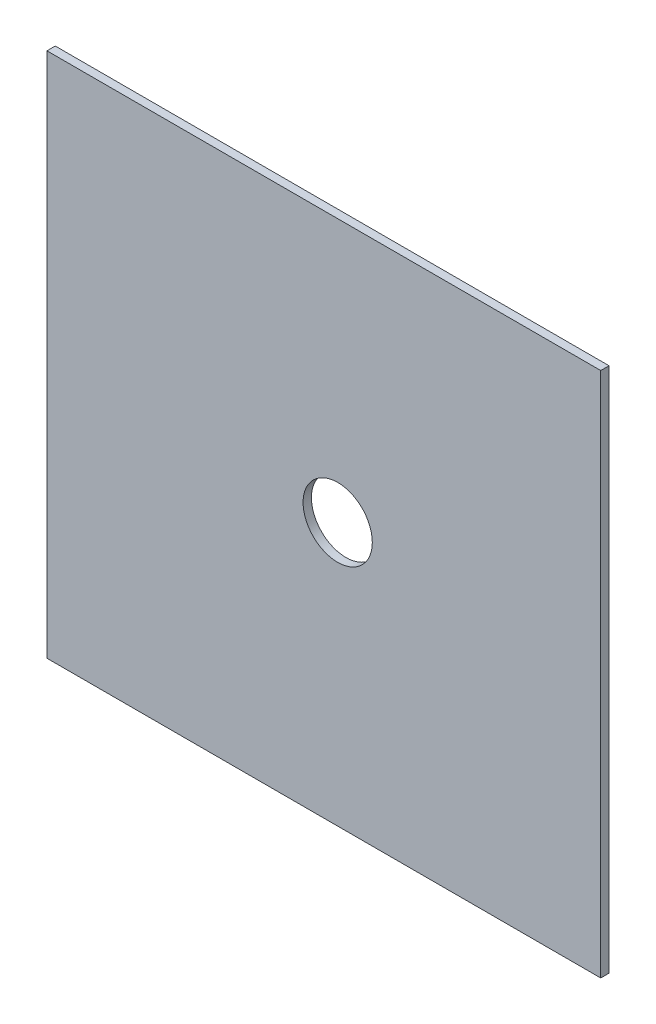
SolidWorks part; units mm, degrees
ref_plane "Alzado" through (0, 0, 0) normal (0, 0, 1) x (1, 0, 0)
ref_plane "Planta" through (0, 0, 0) normal (0, 1, 0) x (1, 0, 0)
ref_plane "Vista lateral" through (0, 0, 0) normal (1, 0, 0) x (0, 0, -1)
sketch "Croquis1" plane through (0, 0, 0) normal (0, 0, 1) x (1, 0, 0)
  line L1 (-100, -95) -> (100, -95)
  line L2 (-100, -95) -> (-100, 95)
  line L3 (-100, 95) -> (100, 95)
  line L4 (100, -95) -> (100, 95)
  line L5 (-100, -95) -> (100, 95) construction
  line L6 (-100, 95) -> (100, -95) construction
  point P0 (0, 0)
  dimension "D1" = 190
  dimension "D2" = 200
extrude "Saliente-Extruir1" add sketch "Croquis1" along normal blind 3
sketch "Croquis2" plane through (0, 0, 3) normal (0, 0, 1) x (1, 0, 0)
  line L0 (100, 0) -> (5, 0) construction
  line L1 (100, -95) -> (100, 95) construction
  circle A0 centre (5, 0) radius 12.5
  dimension "D2" = 25
  dimension "D1" = 95
extrude "Cortar-Extruir1" cut sketch "Croquis2" against normal blind 3
